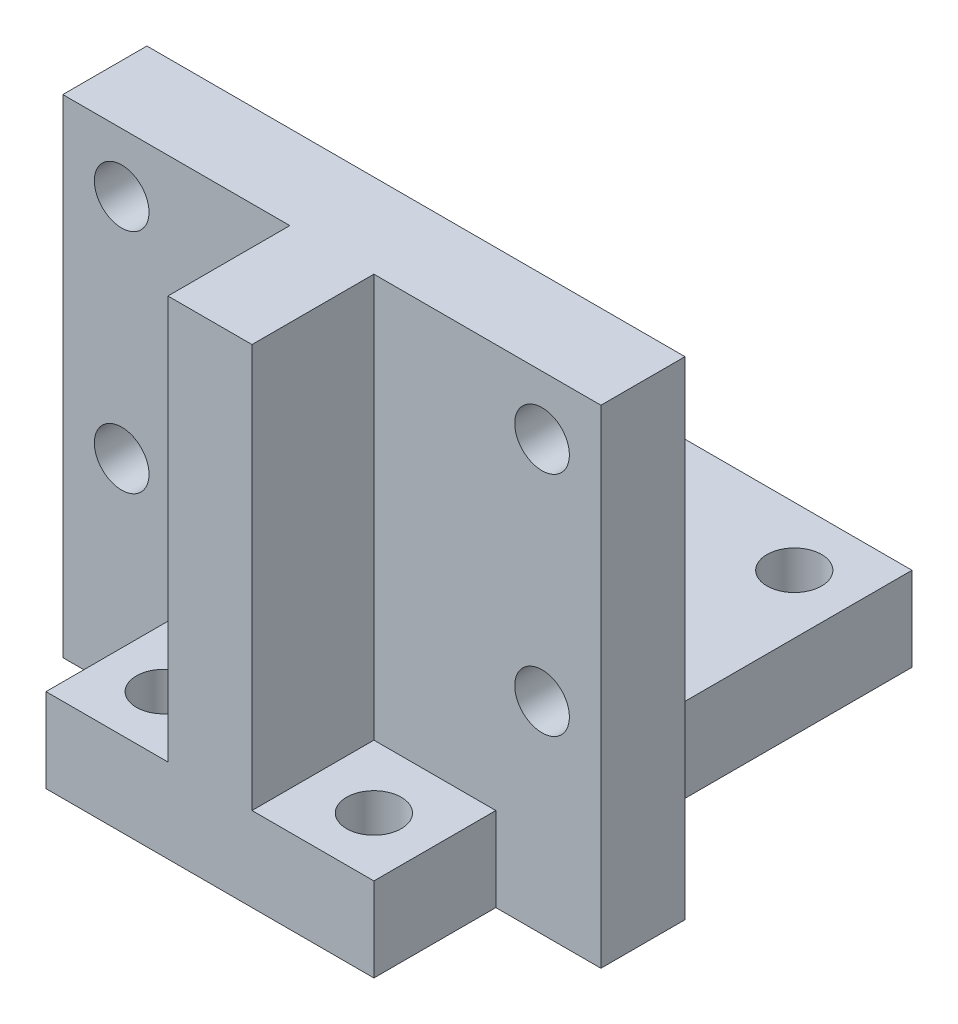
SolidWorks part; units mm, degrees
other "Markup1"
sketch "Sketch6" plane through (-12.5, 56, -51.5) normal (-0.4594, 0.8874, -0.0377) x (0.8843, 0.4609, 0.0741)
ref_plane "Front Plane" through (0, 0, 0) normal (0, 0, 1) x (1, 0, 0)
ref_plane "Top Plane" through (0, 0, 0) normal (0, 1, 0) x (1, 0, 0)
ref_plane "Right Plane" through (0, 0, 0) normal (1, 0, 0) x (0, 0, -1)
sketch "Sketch1" plane through (0, 0, 0) normal (0, 1, 0) x (1, 0, 0)
  line L0 (19.5, 39) -> (19.5, 0) construction
  line L1 (0, 0) -> (39, 0)
  line L2 (0, 0) -> (0, 39)
  line L3 (0, 39) -> (39, 39)
  line L4 (39, 0) -> (39, 39)
  line L5 (0, 19.5) -> (39, 19.5) construction
  circle A0 centre (7, 32) radius 3.25
  circle A1 centre (32, 32) radius 3.25
  circle A2 centre (32, 7) radius 3.25
  circle A3 centre (7, 7) radius 3.25
  dimension "D1" = 6.5
  dimension "D2" = 25
  dimension "D3" = 25
  dimension "D4" = 7
  dimension "D5" = 7
extrude "Boss-Extrude1" add sketch "Sketch1" along normal blind 10
ref_plane "Plane1" through (0, 0, -19.5) normal (0, 0, 1) x (1, 0, 0)
sketch "Sketch2" plane through (0, 0, -19.5) normal (0, 0, 1) x (1, 0, 0)
  line L0 (0, 10) -> (39, 10) construction
  line L1 (-12.5, 0) -> (51.5, 0)
  line L2 (-12.5, 0) -> (-12.5, 58)
  line L3 (-12.5, 58) -> (51.5, 58)
  line L4 (51.5, 0) -> (51.5, 58)
  line L5 (0, 0) -> (39, 0) construction
  line L7 (-5.5, 51) -> (44.5, 51) construction
  line L8 (-5.5, 51) -> (-5.5, 24) construction
  line L9 (-5.5, 24) -> (44.5, 24) construction
  line L10 (44.5, 51) -> (44.5, 24) construction
  circle A0 centre (-5.5, 51) radius 3.25
  circle A1 centre (44.5, 51) radius 3.25
  circle A2 centre (-5.5, 24) radius 3.25
  circle A3 centre (44.5, 24) radius 3.25
  point P6 (19.5, 10)
  point P7 (19.5, 58)
  point P18 (-5.4065, 11.4728)
  point P19 (19.5, 51)
  dimension "D1" = 6.5
  dimension "D2" = 50
  dimension "D3" = 27
  dimension "D4" = 7
  dimension "D5" = 7
  dimension "D6" = 14
extrude "Boss-Extrude2" add sketch "Sketch2" along normal mid plane 10
sketch "Sketch3" plane through (0, 0, 0) normal (0, 0, 1) x (1, 0, 0)
  line L0 (0, 10) -> (39, 10) construction
  line L1 (14.5, 10) -> (24.5, 10)
  line L2 (14.5, 10) -> (14.5, 58)
  line L3 (14.5, 58) -> (24.5, 58)
  line L4 (24.5, 10) -> (24.5, 58)
  line L5 (0, 0) -> (39, 0) construction
  line L6 (51.5, 58) -> (-12.5, 58) construction
  point P8 (19.5, 0)
  point P9 (19.5, 58)
  dimension "D1" = 10
extrude "Boss-Extrude3" add sketch "Sketch3" against normal up to next
sketch "Sketch5" plane through (0, 10, 0) normal (0, 1, 0) x (1, 0, 0)
  line L0 (39, 24.5) -> (39, 39) construction
  line L1 (0, 39) -> (39, 39)
  line L2 (0, 39) -> (0, 64)
  line L3 (0, 64) -> (39, 64)
  line L4 (39, 39) -> (39, 64)
  circle A0 centre (7, 57) radius 3.25
  circle A1 centre (32, 57) radius 3.25
  circle A2 centre (7, 32) radius 3.25 construction
  circle A3 centre (32, 32) radius 3.25 construction
  circle A4 centre (32, 32) radius 3.25 construction
  circle A5 centre (7, 32) radius 3.25 construction
  point P13 (0, 0)
  point P18 (0, 0)
  point P19 (0, 0)
  dimension "D1" = 25
  dimension "D2" = 7
extrude "Boss-Extrude4" add sketch "Sketch5" against normal up to surface (10 mm away) up to face at (19.5, 0, -19.5)
